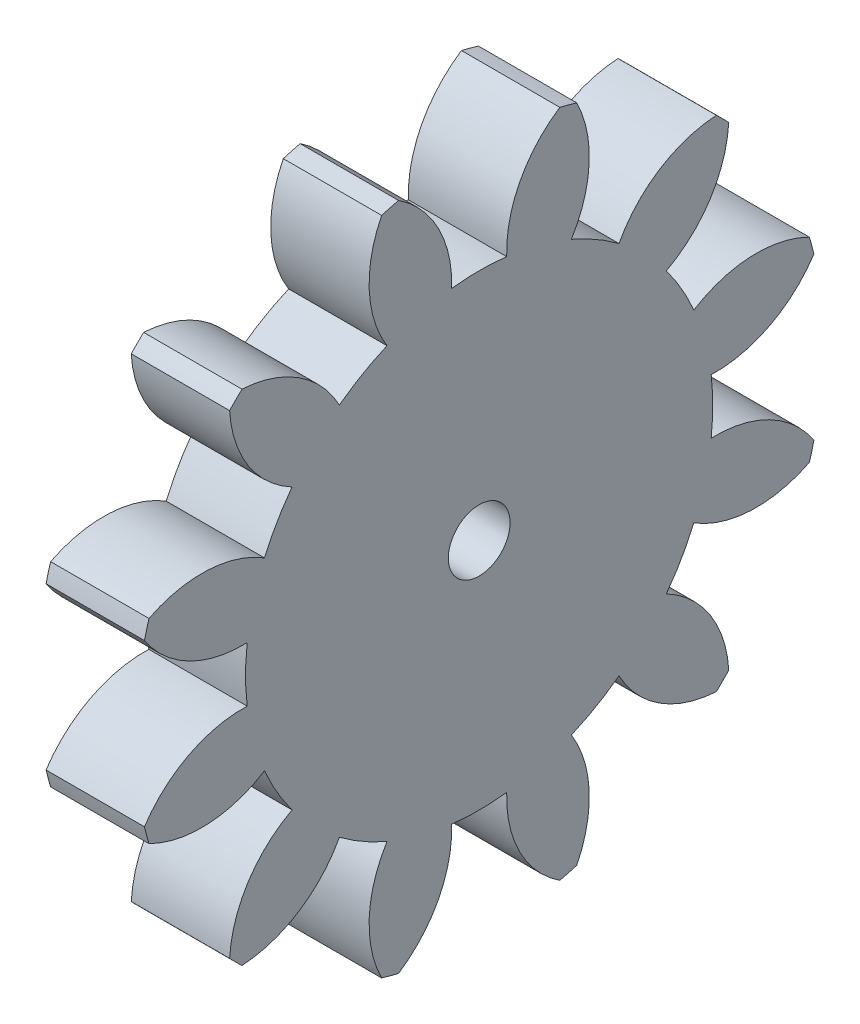
SolidWorks part; units mm, degrees
ref_plane "Plane1" through (0, 0, 0) normal (0, 0, 1) x (1, 0, 0)
ref_plane "Plane2" through (0, 0, 0) normal (0, 1, 0) x (1, 0, 0)
ref_plane "Plane3" through (0, 0, 0) normal (1, 0, 0) x (0, 0, -1)
sketch "HoldingSke" plane through (0, 0, 0) normal (0, 1, 0) x (1, 0, 0)
  line L0 (0, 0) -> (98.996, -22.855)
  line L1 (-15, 0) -> (100, 0) construction
  line L2 (0, 0) -> (-2.1039, 2.3779)
  line L3 (0, 0) -> (-11.863, 4.5341)
  line L4 (0, 0) -> (8.4473, 1.7955)
  line L5 (0, 0) -> (-23.7986, -8.8762)
  line L6 (0, 0) -> (-10.5278, -7.1032)
  line L7 (-2.1039, 2.3779) -> (3.3635, 27.1825)
  line L8 (-76.2, 54.61) -> (-54.61, 54.61)
  line L9 (-71.009, 38.7566) -> (-53.1078, 45.2721)
  line L10 (-76.2, 71.12) -> (104.1128, 71.12)
  line L11 (0, 0) -> (-12.7, 0)
  line L12 (-76.2, 101.6) -> (-75.9714, 101.6)
  line L13 (24.9733, 27.94) -> (52.9518, 28.4284)
  line L14 (24.9733, 27.94) -> (24.9746, 27.94)
  line L15 (24.9733, 27.94) -> (100.4006, 29.5858)
  circle A0 centre (0, 0) radius 9.525
  circle A1 centre (0, 0) radius 12.7
  circle A2 centre (0, 0) radius 12.7
  circle A3 centre (0, 0) radius 9.525
  dimension "MHD" = 25.4
  dimension "Hub_dia" = 25.4
  dimension "Bore" = 19.05
  dimension "MBD" = 19.05
  dimension "Num_teeth" = 12
  dimension "Pitch" = 101.6
  dimension "Overall_len" = 25.4
  dimension "Show_teeth" = 13
  dimension "Thickness" = 12.7
  dimension "OAL" = 25.4001
  dimension "T_dim" = 21.59
  dimension "Ap" = 20
  dimension "H" = 19.05
  dimension "Pitch_radius" = 180.3128
  dimension "Width" = 12.7
  dimension "Backlash" = 0.2286
  dimension "Addendum_fac" = 1
  dimension "Dedendum_fac" = 1.25
  dimension "Clearance_fac" = 0.25
  dimension "Dedendum_add" = 0.0013
sketch "BasProSke" plane through (0, 0, 0) normal (0, 1, 0) x (1, 0, 0)
  line L0 (-10, 0) -> (60, 0) construction
  line L1 (0, 0) -> (0, 44.45)
  line L2 (0, 0) -> (12.7, 0)
  line L3 (12.7, 0) -> (12.7, 44.45)
  line L4 (12.7, 44.45) -> (0, 44.45)
  dimension "Thickness" = 12.7
  dimension "D1" = 44.45
revolve "Base-Revolve" add sketch "BasProSke" angle 360 about L0
sketch "TooCutSke" plane through (0, 0, 0) normal (1, 0, 0) x (0, 0, -1)
  line L1 (0, 0) -> (0, 107) construction
  line L2 (0, 0) -> (-5.3725, 37.7193) construction
  line L3 (0, 0) -> (-19.5794, 73.0714) construction
  line L4 (-5.3725, 37.7193) -> (-9.7897, 36.5357) construction
  arc A0 (3.5522, 29.9513) -> (-3.5522, 29.9513) centre (0, 0) ccw
  arc A1 (10.4397, 43.2328) -> (-10.4397, 43.2328) centre (0, 0) ccw
  circle A2 centre (0, 0) radius 38.1 construction
  circle A3 centre (0, 0) radius 35.8023 construction
  arc A4 (-3.5522, 29.9513) -> (-10.4397, 43.2328) centre (-18.7831, 30.4795) ccw
  arc A5 (10.4397, 43.2328) -> (3.5522, 29.9513) centre (18.7831, 30.4795) ccw
  dimension "Root_dia" = 60.3225
  dimension "Overcut_dia" = 88.9508
  dimension "Pitch_dia" = 76.2
  dimension "Base_dia" = 71.6046
  dimension "Flank_rad" = 15.24
  dimension "Half_ang" = 15
  dimension "Half_CT" = 4.573
extrude "ToothCut" cut sketch "TooCutSke" along normal through all
fillet "Breaks" [suppressed] radius 0.127
fillet "RootFillets" [suppressed] radius 1.5888
pattern_circular "TeethCuts" count 12 over 360 about axis through (0, 0, 0) along (1, 0, 0) of "ToothCut", "RootFillets", "Breaks"
sketch "HubNeaOneSke" plane through (0, 0, 0) normal (-1, 0, 0) x (0, 0, 1)
  circle A0 centre (0, 0) radius 12.7
  dimension "Diameter" = 25.4
extrude "HubNearOne" [suppressed] add sketch "HubNeaOneSke" along normal blind 12.7001
sketch "HubNeaBotSke" plane through (0, 0, 0) normal (-1, 0, 0) x (0, 0, 1)
  circle A0 centre (0, 0) radius 12.7
  dimension "Diameter" = 25.4
extrude "HubNearBoth" [suppressed] add sketch "HubNeaBotSke" along normal blind 6.35
ref_plane "FarPln" through (12.7, 0, 0) normal (1, 0, 0) x (0, 0, -1)
sketch "HubFarSke" plane through (12.7, 0, 0) normal (1, 0, 0) x (0, 0, -1)
  circle A0 centre (0, 0) radius 12.7
  dimension "Diameter" = 25.4
extrude "HubFar" [suppressed] add sketch "HubFarSke" along normal blind 6.35
sketch "BorSke" plane through (0, 0, 0) normal (1, 0, 0) x (0, 0, -1)
  circle A0 centre (0, 0) radius 3.9878
  dimension "D1" = 7.9756
extrude "Bore" cut sketch "BorSke" along normal mid plane 50.8001
sketch "KeySke" plane through (0, 0, 0) normal (1, 0, 0) x (0, 0, -1)
  line L0 (-3.175, 0) -> (-3.175, 12.065)
  line L1 (-3.175, 12.065) -> (3.175, 12.065)
  line L2 (3.175, 12.065) -> (3.175, 0)
  line L3 (0, 0) -> (0, 34) construction
  line L4 (-3.175, 0) -> (3.175, 0)
  dimension "Offset" = 12.065
  dimension "Width" = 6.35
extrude "Keyway" [suppressed] cut sketch "KeySke" along normal mid plane 50.8001
pattern_circular "Keyway2" [suppressed] count 2 every 90 about axis through (-10, 0, 0) along (1, 0, 0)
equation "' \"Pitch@HoldingSke\" = 4"
equation "' \"Num_teeth@HoldingSke\" = 12"
equation "' \"Ap@HoldingSke\" =  20"
equation "' \"Ap@HoldingSke\" = 20"
equation "' \"Width@HoldingSke\" = 0.5"
equation "' \"Hub_dia@HoldingSke\"= 1"
equation "' \"Hub_dia@HoldingSke\" = 1"
equation "' \"Overall_len@HoldingSke\" = 1.0"
equation "' \"Bore@HoldingSke\" = 0.75"
equation "' \"T_dim@HoldingSke\" = 0.85"
equation "' \"Width@KeySke\" = 0.25"
equation "' \"Show_teeth@HoldingSke\" = 13"
equation "' \"Backlash@HoldingSke\" = 0.009"
equation "' \"Addendum_fac@HoldingSke\" = 1.0"
equation "' \"Dedendum_fac@HoldingSke\" = 1.25"
equation "' \"Dedendum_add@HoldingSke\" = 0.00005"
equation "' \"Clearance_fac@HoldingSke\" = 0.25"
equation "' \"Pitch@HoldingSke\" = 0.5"
equation "' \"Num_teeth@HoldingSke\" = 23"
equation "' \"Show_teeth@HoldingSke\" = 23"
equation "' \"Backlash@HoldingSke\" = 0.0375"
equation "\"Overcut_dia@TooCutSke\" = (\"Num_teeth@HoldingSke\" + 2 * \"Addendum_fac@HoldingSke\") / \"Pitch@HoldingSke\" + 0.002"
equation "\"Pitch_dia@TooCutSke\" = \"Num_teeth@HoldingSke\" / \"Pitch@HoldingSke\""
equation "\"Base_dia@TooCutSke\" = \"Num_teeth@HoldingSke\" / \"Pitch@HoldingSke\" * cos((\"Ap@HoldingSke\"  * 3.14159265 / 180))"
equation "\"Root_dia@TooCutSke\" = (\"Num_teeth@HoldingSke\" + 2) / \"Pitch@HoldingSke\" - 2 * (\"Addendum_fac@HoldingSke\" + \"Dedendum_fac@HoldingSke\") / \"Pitch@HoldingSke\" - \"Dedendum_add@HoldingSke\" * 2"
equation "\"Half_ang@TooCutSke\" = 180 / \"Num_teeth@HoldingSke\""
equation "\"Half_CT@TooCutSke\" = \"Num_teeth@HoldingSke\" / \"Pitch@HoldingSke\" * sin((3.14159265 / 2 / \"Num_teeth@HoldingSke\")) / 2 - 7 * \"Backlash@HoldingSke\" / 4"
equation "\"Flank_rad@TooCutSke\" = \"Num_teeth@HoldingSke\" / \"Pitch@HoldingSke\" / 5"
equation "\"Radius@RootFillets\" = \"Clearance_fac@HoldingSke\" / \"Pitch@HoldingSke\" + \"Dedendum_add@HoldingSke\""
equation "\"Break_rad@Breaks\" = 0.02 / \"Pitch@HoldingSke\""
equation "\"Thickness@HoldingSke\" = \"Width@HoldingSke\""
equation "\"OAL@HoldingSke\" = \"Thickness@HoldingSke\""
equation "\"MHD@HoldingSke\" = (\"Num_teeth@HoldingSke\" + 2) / \"Pitch@HoldingSke\" - 2 * (\"Addendum_fac@HoldingSke\" + \"Dedendum_fac@HoldingSke\")  / \"Pitch@HoldingSke\" - \"Dedendum_add@HoldingSke\" * 2"
equation "\"MBD@HoldingSke\" = (\"Num_teeth@HoldingSke\" + 2) / \"Pitch@HoldingSke\" - 2 * (\"Addendum_fac@HoldingSke\" + \"Dedendum_fac@HoldingSke\")  / \"Pitch@HoldingSke\" - \"Dedendum_add@HoldingSke\" * 2 - 0.002"
equation "\"MHD@HoldingSke\" = ((sgn( \"MHD@HoldingSke\" - \"Hub_dia@HoldingSke\" )-1)*( \"MHD@HoldingSke\" - \"Hub_dia@HoldingSke\" ))/-2+ \"Hub_dia@HoldingSke\""
equation "\"MBD@HoldingSke\" = ((sgn( \"MBD@HoldingSke\" - \"Bore@HoldingSke\" )-1)*( \"MBD@HoldingSke\" - \"Bore@HoldingSke\" ))/-2+ \"Bore@HoldingSke\""
equation "\"OAL@HoldingSke\" = ((sgn( \"OAL@HoldingSke\" - \"Overall_len@HoldingSke\" )+1)*( \"OAL@HoldingSke\" - \"Overall_len@HoldingSke\" ))/2 + \"Overall_len@HoldingSke\" + 0.000002"
equation "\"Num_teeth@TeethCuts\" = int( \"Show_teeth@HoldingSke\" ) + 1"
equation "\"Num_teeth@TeethCuts\" = ((sgn( \"Num_teeth@TeethCuts\" - \"Num_teeth@HoldingSke\" )-1)*( \"Num_teeth@TeethCuts\" - \"Num_teeth@HoldingSke\" ))/-2+ \"Num_teeth@HoldingSke\""
equation "\"Num_teeth@TeethCuts\" = ((sgn( \"Num_teeth@TeethCuts\" - 2.0)+1)*( \"Num_teeth@TeethCuts\" - 2.0))/2 +2.0"
equation "\"Angle@TeethCuts\" = 360.0 / \"Num_teeth@HoldingSke\""
equation "\"Thickness@BasProSke\"  = \"Thickness@HoldingSke\""
equation "' \"Fillet_rad@BasProSke\" =  \"Thickness@HoldingSke\" * 0.05"
equation "' \"Fillet_rad@BasProSke\" = \"Thickness@HoldingSke\" * 0.05"
equation "\"MHD@HoldingSke\" = ((sgn( \"MHD@HoldingSke\" - \"Root_dia@TooCutSke\" )-1)*( \"MHD@HoldingSke\" - \"Root_dia@TooCutSke\" ))/-2+ \"Root_dia@TooCutSke\""
equation "\"Diameter@HubNeaOneSke\" = \"MHD@HoldingSke\""
equation "\"Length@HubNearOne\" = \"OAL@HoldingSke\" - \"Thickness@BasProSke\""
equation "\"Diameter@HubNeaBotSke\" = \"MHD@HoldingSke\""
equation "\"Length@HubNearBoth\" = ( \"OAL@HoldingSke\" - \"Thickness@BasProSke\" ) / 2.0"
equation "\"Thickness\" = \"Thickness@BasProSke\""
equation "\"Diameter@HubFarSke\" = \"MHD@HoldingSke\""
equation "\"Length@HubFar\" = ( \"OAL@HoldingSke\" - \"Thickness@BasProSke\" ) / 2.0"
equation "\"D1@Bore\" = \"OAL@HoldingSke\" * 2.0"
equation "\"D1@Keyway\" = \"OAL@HoldingSke\" * 2.0"
equation "\"Offset@KeySke\" = \"T_dim@HoldingSke\" - \"MBD@HoldingSke\" / 2.0"
